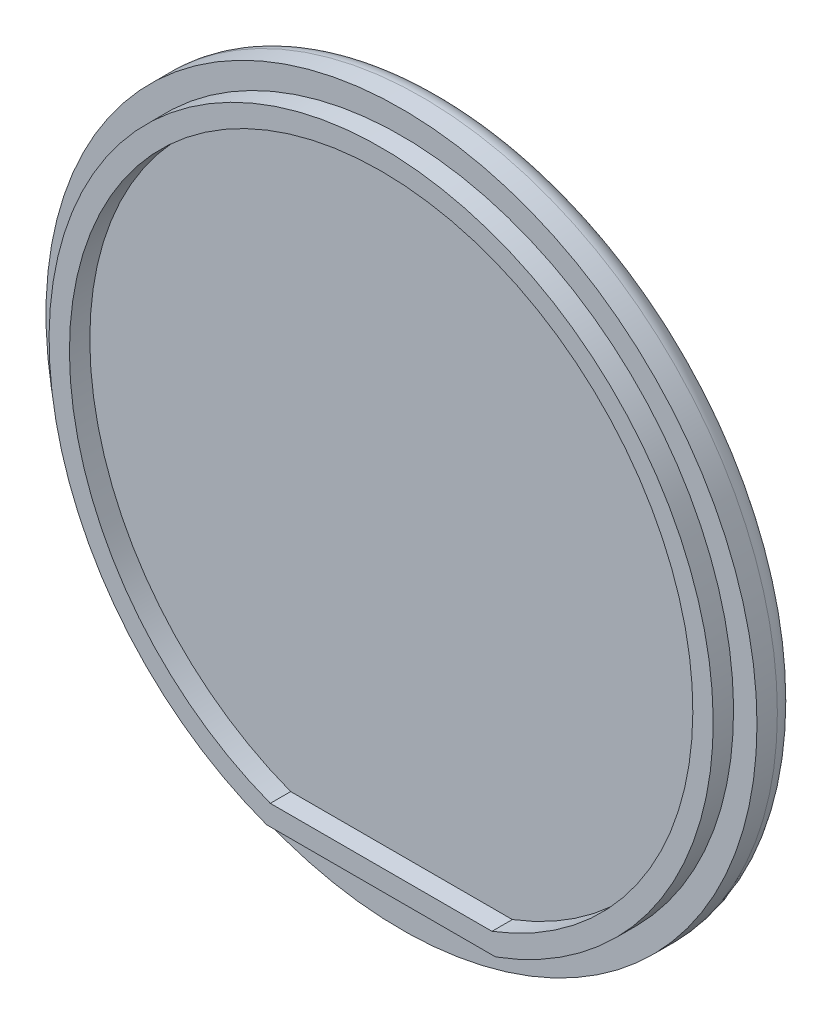
SolidWorks part; units mm, degrees
ref_plane "Plan de face" through (0, 0, 0) normal (0, 0, 1) x (1, 0, 0)
ref_plane "Plan de dessus" through (0, 0, 0) normal (0, 1, 0) x (1, 0, 0)
ref_plane "Plan de droite" through (0, 0, 0) normal (1, 0, 0) x (0, 0, -1)
sketch "Esquisse1" plane through (0, 0, 0) normal (0, 0, 1) x (1, 0, 0)
  circle A0 centre (0, 0) radius 34.9
  point P2 (0, 0)
  dimension "D1" = 69.8
extrude "Boss.-Extru.1" add sketch "Esquisse1" along normal blind 4
sketch "Esquisse2" plane through (0, 0, 4) normal (0, 0, 1) x (1, 0, 0)
  line L0 (-11.2418, -30.6004) -> (11.2418, -30.6004)
  line L1 (-10.8802, -28.6004) -> (10.8802, -28.6004)
  line L2 (-11.295, -30.9004) -> (11.295, -30.9004) construction
  circle A0 centre (0, 0) radius 32.9 construction
  circle A1 centre (0, 0) radius 30.6 construction
  circle A2 centre (0, 0) radius 32.6 construction
  arc A3 (-11.2418, -30.6004) -> (11.2418, -30.6004) centre (0, 0) cw
  arc A4 (-10.8802, -28.6004) -> (10.8802, -28.6004) centre (0, 0) cw
  point P11 (0, -30.9004)
  dimension "D1" = 22.59
  dimension "D2" = 65.8
  dimension "D3" = 65.2
  dimension "D4" = 61.2
  dimension "D6" = 2
  dimension "D7" = 2
  dimension "D5" = 0.3
sketch "Esquisse4" plane through (0, 0, 0) normal (0, 0, -1) x (-1, 0, 0)
  line L0 (0, 34.9) -> (0, -34.9) construction
  line L1 (-34.9, 0) -> (34.9, 0) construction
  line L2 (1.5, 7.5) -> (1.5, -7.5)
  line L3 (-4.5, 7.5) -> (-1.5, 7.5)
  line L4 (-4.5, 7.5) -> (-4.5, -7.5)
  line L5 (-4.5, -7.5) -> (-1.5, -7.5)
  line L6 (-1.5, 7.5) -> (-1.5, -7.5)
  line L7 (4.5, -7.5) -> (1.5, -7.5)
  line L8 (4.5, 7.5) -> (4.5, -7.5)
  line L9 (4.5, 7.5) -> (1.5, 7.5)
  circle A0 centre (0, 0) radius 34.9 construction
  point P7 (0, 0)
  point P13 (-4.5, 0)
  dimension "D1" = 3
  dimension "D2" = 15
  dimension "D3" = 1.5
extrude "Boss.-Extru.3" add sketch "Esquisse4" along normal blind 20
sketch "Esquisse5" plane through (4.5, 0, 0) normal (1, 0, 0) x (0, 0, -1)
  line L0 (8.44, 7.5) -> (8.44, -7.5) construction
  line L1 (8.44, 7.5) -> (20, 7.5)
  line L2 (20, 7.5) -> (20, -7.5)
  line L3 (20, -7.5) -> (8.44, -7.5)
  line L4 (20, 7.5) -> (0, 7.5) construction
  line L5 (20, -7.5) -> (0, -7.5) construction
  line L10 (0, 7.5) -> (0, -7.5) construction
  arc A0 (8.44, 7.5) -> (8.44, -7.5) centre (8.44, 0) cw
  dimension "D1" = 8.44
extrude "Enlèv. mat.-Extru.2" cut sketch "Esquisse5" against normal through all
fillet "Congé1" radius 5 6 edges at (-3, 7.5, 0) (-3, -7.5, 0) (-4.5, 0, 0) (3, 7.5, 0) (3, -7.5, 0) (4.5, 0, 0)
sketch "Esquisse6" plane through (4.5, 0, 0) normal (1, 0, 0) x (0, 0, -1)
  circle A0 centre (8.44, 0) radius 2.5
  arc A1 (8.44, -7.5) -> (8.44, 7.5) centre (8.44, 0) ccw construction
  point P9 (15.94, 0)
  dimension "D1" = 5
  dimension "D2" = 7.5
  dimension "D3" = 7.5
extrude "Enlèv. mat.-Extru.3" cut sketch "Esquisse6" against normal through all
extrude "Boss.-Extru.4" add sketch "Esquisse2" along normal blind 2 contours A3 L0 L1 A4
fillet "Congé2" radius 2 1 edges at (34.9, 0, 0)
